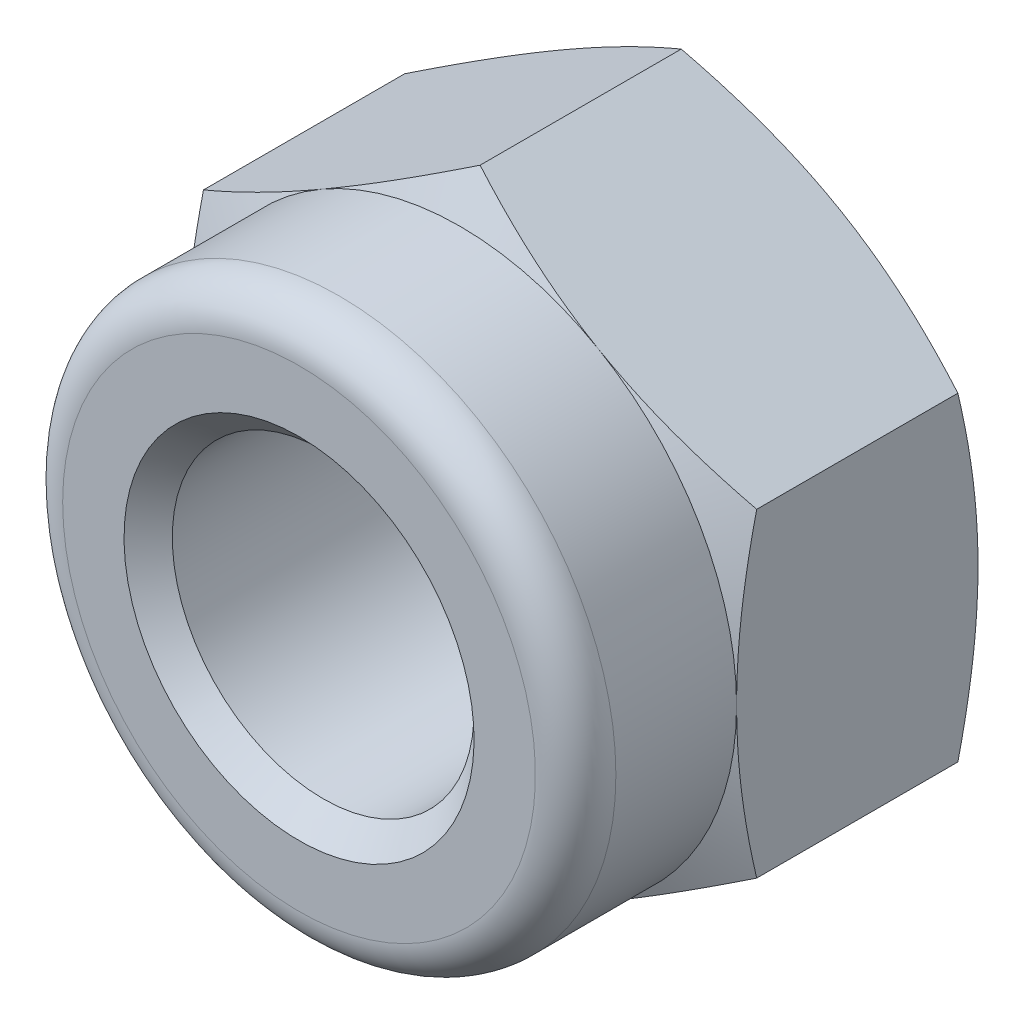
SolidWorks part; units mm, degrees
material "Plain Carbon Steel"
ref_plane "Front Plane" through (0, 0, 0) normal (0, 0, 1) x (1, 0, 0)
ref_plane "Top Plane" through (0, 0, 0) normal (0, 1, 0) x (1, 0, 0)
ref_plane "Right Plane" through (0, 0, 0) normal (1, 0, 0) x (0, 0, -1)
sketch "Sketch1" plane through (0, 0, 0) normal (0, 0, 1) x (1, 0, 0)
  line L1 (0, -3.1754) -> (2.75, -1.5877)
  line L2 (2.75, -1.5877) -> (2.75, 1.5877)
  line L3 (2.75, 1.5877) -> (0, 3.1754)
  line L4 (0, 3.1754) -> (-2.75, 1.5877)
  line L5 (-2.75, 1.5877) -> (-2.75, -1.5877)
  line L6 (-2.75, -1.5877) -> (0, -3.1754)
  circle A0 centre (0, 0) radius 2.75 construction
  circle A1 centre (0, 0) radius 1.5
  dimension "D2" = 3
  dimension "D1" = 5.5
extrude "Boss-Extrude1" add sketch "Sketch1" along normal blind 2.4
sketch "Sketch3" plane through (0, 0, 0) normal (0, 1, 0) x (0, 0, -1)
  line L0 (-2.4, 2.75) -> (-3.6, 2.75)
  line L1 (-2.4, -2.75) -> (-2.4, 0) construction
  line L2 (-4, 2.35) -> (-4, 1.5)
  line L3 (-4, 1.5) -> (-2.4, 1.5)
  line L5 (-2.4, 1.5) -> (-2.4, 2.75)
  line L6 (0, 0) -> (-2.4, 0) construction
  arc A0 (-3.6, 2.75) -> (-4, 2.35) centre (-3.6, 2.35) ccw
  dimension "D1" = 0.4
  dimension "D2" = 4
revolve "Revolve1" add sketch "Sketch3" angle 360 about L6
sketch "Sketch2" plane through (0, 0, 0) normal (1, 0, 0) x (0, 0, -1)
  line L0 (-2.4, 3.1754) -> (-2.4, 2.75)
  line L1 (-2.4, 1.5877) -> (-2.4, 2.3816) construction
  line L2 (-2.4, 2.75) -> (-2.2, 3.1754)
  line L3 (-2.4, 3.1754) -> (0, 3.1754) construction
  line L4 (-2.2, 3.1754) -> (-2.4, 3.1754)
  line L5 (-0.2, 3.1754) -> (0, 3.1754)
  line L6 (0, 3.1754) -> (0, 2.75)
  line L7 (0, 1.5877) -> (0, 3.1754) construction
  line L8 (0, 2.75) -> (-0.2, 3.1754)
  line L9 (-2.2, 3.1754) -> (-2, 3.1754) construction
  line L10 (-2, 3.1754) -> (-1.8, 3.1754) construction
  line L11 (-1.8, 3.1754) -> (-1.6, 3.1754) construction
  line L12 (-1.6, 3.1754) -> (-1.4, 3.1754) construction
  line L13 (-1.4, 3.1754) -> (-1.2, 3.1754) construction
  line L14 (-1.2, 3.1754) -> (-1, 3.1754) construction
  line L15 (-1, 3.1754) -> (-0.8, 3.1754) construction
  line L16 (-0.8, 3.1754) -> (-0.6, 3.1754) construction
  line L17 (-0.6, 3.1754) -> (-0.4, 3.1754) construction
  line L18 (0, 0) -> (-2.4, 0) construction
  line L20 (-4, 1.5) -> (-3.76, 1.5)
  line L21 (-3.76, 1.5) -> (-4, 1.74)
  line L22 (-4, 1.74) -> (-4, 1.5)
  line L23 (0, 1.5) -> (-0.24, 1.5)
  line L24 (0, -1.5877) -> (0, 1.5877) construction
  line L25 (-0.24, 1.5) -> (0, 1.74)
  line L26 (0, 1.74) -> (0, 1.5)
  line L27 (-4, 2.35) -> (-4, -2.35) construction
  line L28 (-1.92, 1.5) -> (-2.16, 1.5) construction
  line L29 (-2.16, 1.5) -> (-2.4, 1.5) construction
  line L30 (-1.92, 1.5) -> (-1.68, 1.5) construction
  line L31 (-1.68, 1.5) -> (-1.44, 1.5) construction
  line L32 (-1.44, 1.5) -> (-1.2, 1.5) construction
  line L33 (-1.2, 1.5) -> (-0.96, 1.5) construction
  line L34 (-0.96, 1.5) -> (-0.72, 1.5) construction
  line L35 (-0.72, 1.5) -> (-0.48, 1.5) construction
  line L36 (-0.48, 1.5) -> (-0.24, 1.5) construction
  line L37 (-0.4, 3.1754) -> (-0.2, 3.1754) construction
  line L38 (-2.4, 0) -> (-2.4, 1.5877) construction
  dimension "D1" = 5.5
revolve "Cut-Revolve1" cut sketch "Sketch2" angle 360 about L18
